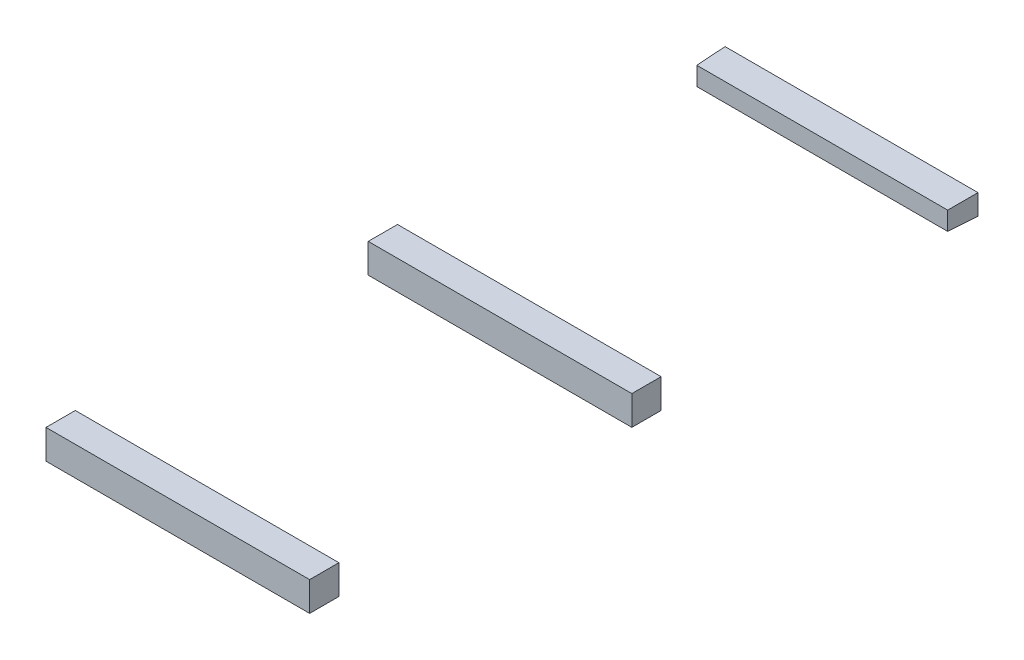
SolidWorks part; units mm, degrees
ref_plane "Front Plane" through (0, 0, 0) normal (0, 0, 1) x (1, 0, 0)
ref_plane "Top Plane" through (0, 0, 0) normal (0, 1, 0) x (1, 0, 0)
ref_plane "Right Plane" through (0, 0, 0) normal (1, 0, 0) x (0, 0, -1)
sketch "Sketch1" plane through (0, 0, 0) normal (0, 0, 1) x (1, 0, 0)
  line L0 (-43.175, 0) -> (43.175, 0)
  line L1 (43.175, 0) -> (43.175, -7)
  line L2 (43.175, -7) -> (-43.175, -7)
  line L3 (-43.175, -7) -> (-43.175, 0)
  point P4 (0, 0)
  dimension "D1" = 86.35
  dimension "D2" = 7
extrude "Boss-Extrude1" add sketch "Sketch1" along normal blind 10 draft 2
sketch "Sketch2" plane through (0, 0, 0) normal (1, 0, 0) x (0, 0, -1)
  line L0 (0, -3.5) -> (-10, -3.5)
  line L1 (0, -7) -> (0, 0) construction
  line L2 (-10, -6.6508) -> (-10, -0.3492) construction
  line L3 (-10, -3.5) -> (-110, -3.5)
  line L4 (-120, -3.5) -> (-220, -3.5)
  line L5 (-110, -8.5) -> (-110, 1.5)
  line L6 (-110, 1.5) -> (-120, 1.5)
  line L7 (-110, 1.5) -> (-110, -8.5)
  line L8 (-110, -8.5) -> (-120, -8.5)
  line L9 (-120, 1.5) -> (-120, -8.5)
  line L10 (-220, -8.5) -> (-220, 1.5)
  line L12 (-220, 1.5) -> (-230, 1.5)
  line L13 (-220, 1.5) -> (-220, -8.5)
  line L14 (-220, -8.5) -> (-230, -8.5)
  line L15 (-230, 1.5) -> (-230, -8.5)
  point P10 (-110, -3.5)
  point P13 (-110, -3.5)
  point P18 (-220, -3.5)
  dimension "D1" = 100
  dimension "D2" = 10
  dimension "D3" = 10
  dimension "D4" = 100
  dimension "D5" = 10
  dimension "D6" = 10
extrude "Boss-Extrude2" add sketch "Sketch2" along normal mid plane 90 separate body contours L6 L9 L8 L5 | L13 L12 L15 L14
